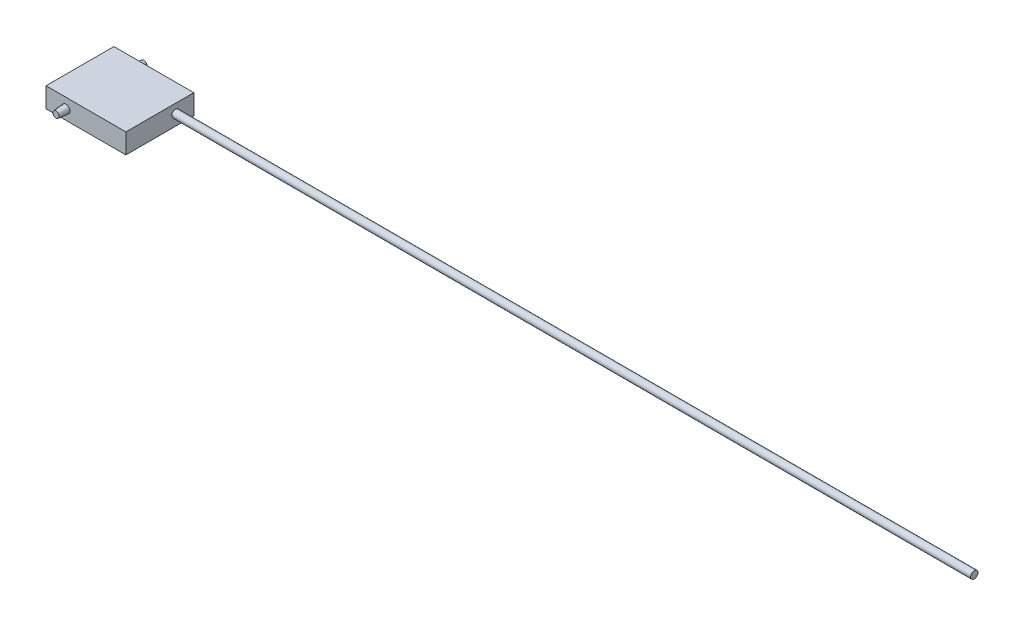
SolidWorks part; units mm, degrees
ref_plane "Front Plane" through (0, 0, 0) normal (0, 0, 1) x (1, 0, 0)
ref_plane "Top Plane" through (0, 0, 0) normal (0, 1, 0) x (1, 0, 0)
ref_plane "Right Plane" through (0, 0, 0) normal (1, 0, 0) x (0, 0, -1)
sketch "Sketch1" plane through (0, 0, 0) normal (0, 1, 0) x (1, 0, 0)
  line L1 (-12.7, -10.795) -> (12.7, -10.795)
  line L2 (-12.7, -10.795) -> (-12.7, 10.795)
  line L3 (-12.7, 10.795) -> (12.7, 10.795)
  line L4 (12.7, -10.795) -> (12.7, 10.795)
  line L5 (-12.7, -10.795) -> (12.7, 10.795) construction
  line L6 (-12.7, 10.795) -> (12.7, -10.795) construction
  point P0 (0, 0)
  dimension "D1" = 25.4
  dimension "D2" = 21.59
extrude "Boss-Extrude1" add sketch "Sketch1" along normal blind 6.35
sketch "Sketch2" plane through (0, 0, 10.795) normal (0, 0, 1) x (1, 0, 0)
  line L0 (-12.7, 6.35) -> (-12.7, 0) construction
  circle A0 centre (-6.35, 3.175) radius 1.27
  dimension "D2" = 2.54
  dimension "D1" = 6.35
extrude "Boss-Extrude2" add sketch "Sketch2" along normal blind 3.175 draft 5 contours A0
mirror "Mirror1" about plane through (0, 0, 0) normal (0, 0, 1) of "Boss-Extrude2"
sketch "Sketch3" plane through (12.7, 0, 0) normal (1, 0, 0) x (0, 0, -1)
  circle A0 centre (4.9564, 3.55) radius 1.169
extrude "Boss-Extrude3" add sketch "Sketch3" along normal blind 254
